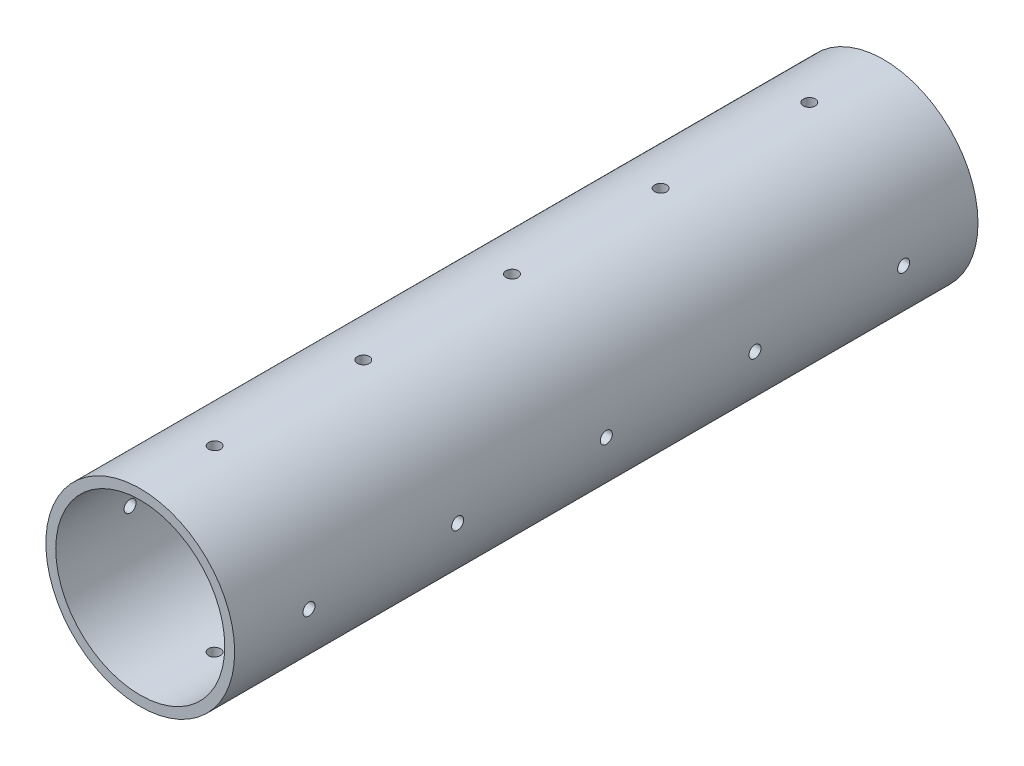
SolidWorks part; units mm, degrees
ref_plane "Front" through (0, 0, 0) normal (0, 0, 1) x (1, 0, 0)
ref_plane "Top" through (0, 0, 0) normal (0, 1, 0) x (1, 0, 0)
ref_plane "Right" through (0, 0, 0) normal (1, 0, 0) x (0, 0, -1)
sketch "Sketch1" plane through (0, 0, 0) normal (0, 0, 1) x (1, 0, 0)
  circle A0 centre (0, 0) radius 15.875
  circle A1 centre (0, 0) radius 14.2108
  dimension "D1" = 31.75
  dimension "D2" = 28.4216
extrude "Boss-Extrude1" add sketch "Sketch1" along normal blind 125
sketch "Sketch2" plane through (0, 0, 0) normal (0, 1, 0) x (1, 0, 0)
  line L0 (0, 0) -> (0, -125) construction
  line L1 (-15.875, -125) -> (15.875, -125) construction
  line L2 (14.2108, 0) -> (-14.2108, 0) construction
  line L3 (-15.875, -62.5) -> (15.875, -62.5) construction
  line L4 (-15.875, 0) -> (-15.875, -125) construction
  line L5 (15.875, -125) -> (15.875, 0) construction
  circle A0 centre (0, -12.5) radius 1.0125
  circle A2 centre (0, -37.5) radius 1.0125
  circle A3 centre (0, -62.5) radius 1.0125
  circle A4 centre (0, -87.5) radius 1.0125
  circle A5 centre (0, -112.5) radius 1.0125
  circle A6 centre (0, -137.5) radius 1.0125
  circle A7 centre (0, -162.5) radius 1.0125
  circle A8 centre (0, -187.5) radius 1.0125
  circle A9 centre (0, -212.5) radius 1.0125
  circle A10 centre (0, -237.5) radius 1.0125
  circle A11 centre (0, -262.5) radius 1.0125
  circle A12 centre (0, -287.5) radius 1.0125
  circle A20 centre (0, -312.5) radius 1.0125 [skipped]
  circle A21 centre (0, -337.5) radius 1.0125 [skipped]
  circle A22 centre (0, -362.5) radius 1.0125 [skipped]
  circle A23 centre (0, -387.5) radius 1.0125 [skipped]
  circle A24 centre (0, -412.5) radius 1.0125 [skipped]
  circle A25 centre (0, -437.5) radius 1.0125 [skipped]
  circle A26 centre (0, -462.5) radius 1.0125 [skipped]
  dimension "D1" = 2.025
  dimension "D2" = 12.5
  dimension "D3" = 2.025
  dimension "D4" = 25
  dimension "D5" = 18
extrude "Cut-Extrude1" cut sketch "Sketch2" against normal up to surface and the other way up to surface up to face at (15.875, 0, 125) other way up to face at (15.875, 0, 125)
sketch "Sketch3" plane through (0, 0, 0) normal (1, 0, 0) x (0, 0, -1)
  line L0 (0, 0) -> (-125, 0) construction
  line L1 (-125, 15.875) -> (-125, -15.875) construction
  line L2 (0, -14.2108) -> (0, 14.2108) construction
  circle A0 centre (-12.5, 0) radius 1.0125
  circle A2 centre (-37.5, 0) radius 1.0125
  circle A3 centre (-62.5, 0) radius 1.0125
  circle A4 centre (-87.5, 0) radius 1.0125
  circle A5 centre (-112.5, 0) radius 1.0125
  circle A6 centre (-137.5, 0) radius 1.0125
  circle A7 centre (-162.5, 0) radius 1.0125
  circle A8 centre (-187.5, 0) radius 1.0125
  circle A9 centre (-212.5, 0) radius 1.0125
  circle A10 centre (-237.5, 0) radius 1.0125
  circle A11 centre (-262.5, 0) radius 1.0125
  circle A12 centre (-287.5, 0) radius 1.0125
  circle A20 centre (-312.5, 0) radius 1.0125 [skipped]
  circle A21 centre (-337.5, 0) radius 1.0125 [skipped]
  circle A22 centre (-362.5, 0) radius 1.0125 [skipped]
  circle A23 centre (-387.5, 0) radius 1.0125 [skipped]
  circle A24 centre (-412.5, 0) radius 1.0125 [skipped]
  circle A25 centre (-437.5, 0) radius 1.0125 [skipped]
  circle A26 centre (-462.5, 0) radius 1.0125 [skipped]
  dimension "D2" = 2.025
  dimension "D3" = 12.5
  dimension "D5" = 2.025
  dimension "D6" = 25
  dimension "D7" = 18
extrude "Cut-Extrude2" cut sketch "Sketch3" against normal up to surface and the other way up to surface up to face at (0.2306, -15.8733, 36.5141) other way up to face at (0.2306, -15.8733, 36.5141)
